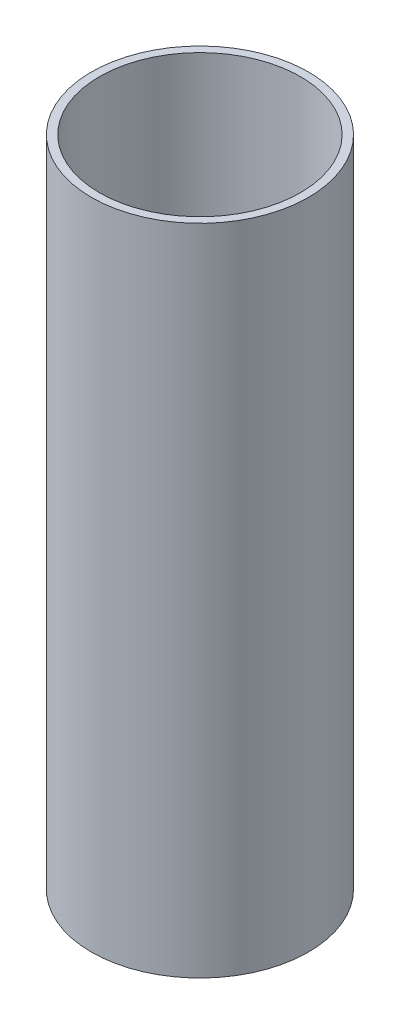
SolidWorks part; units mm, degrees
material "Thornel Mat VMA"
ref_plane "Front Plane" through (0, 0, 0) normal (0, 0, 1) x (1, 0, 0)
ref_plane "Top Plane" through (0, 0, 0) normal (0, 1, 0) x (1, 0, 0)
ref_plane "Right Plane" through (0, 0, 0) normal (1, 0, 0) x (0, 0, -1)
sketch "Sketch2" plane through (0, 0, 0) normal (0, 1, 0) x (1, 0, 0)
  circle A0 centre (0, 0) radius 13.716
  circle A1 centre (0, 0) radius 12.7
  dimension "D1" = 25.4
  dimension "D2" = 1.016
extrude "Boss-Extrude1" add sketch "Sketch2" along normal blind 82.55
